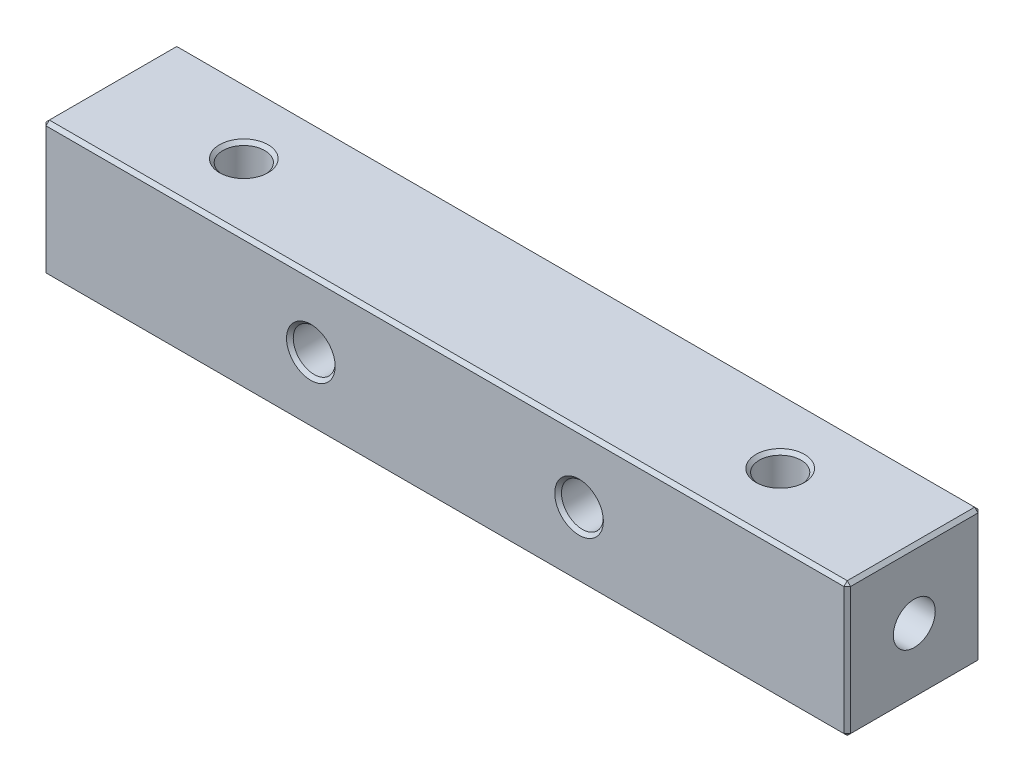
SolidWorks part; units mm, degrees
ref_plane "前视基准面" through (0, 0, 0) normal (0, 0, 1) x (1, 0, 0)
ref_plane "上视基准面" through (0, 0, 0) normal (0, 1, 0) x (1, 0, 0)
ref_plane "右视基准面" through (0, 0, 0) normal (1, 0, 0) x (0, 0, -1)
sketch "草图1" plane through (0, 0, 0) normal (0, 1, 0) x (1, 0, 0)
  line L1 (-24, 4) -> (24, 4)
  line L2 (-24, 4) -> (-24, -4)
  line L3 (-24, -4) -> (24, -4)
  line L4 (24, 4) -> (24, -4)
  line L5 (-24, 4) -> (24, -4) construction
  line L6 (-24, -4) -> (24, 4) construction
  point P0 (0, 0)
  dimension "D1" = 8
  dimension "D2" = 48
extrude "凸台-拉伸1" add sketch "草图1" along normal mid plane 8
hole_wizard "M3 螺纹孔1" positions "草图4" profile "草图6" tap size "M3" standard "GB" end condition through all
sketch "草图4" plane through (0, 4, 0) normal (0, 1, 0) x (1, 0, 0)
  line L0 (-24, 4) -> (-24, -4) construction
  line L1 (0, 0) -> (-50000, 0) construction
  point P0 (-16, 0)
  point P2 (16, 0)
  dimension "D1" = 8
  dimension "D2" = 32
sketch "草图6" plane through (-16, 4, 0) normal (1, 0, 0) x (0, 0, 1)
  line L0 (0, 0) -> (0, 8)
  line L1 (0, 8) -> (1.25, 8)
  line L2 (1.25, 8) -> (1.25, 0)
  line L5 (1.25, 0) -> (0, 0)
  line L11 (0, -6.35) -> (0, 107.95) construction
  dimension "通孔螺纹孔钻头直径" = 2.5
  dimension "通孔螺纹孔钻头深度" = 8
cosmetic thread "孔螺蚊线1"
cosmetic thread "孔螺蚊线2"
hole_wizard "M3 螺纹孔2" positions "草图7" profile "草图8" tap size "M3" standard "GB" end condition through all
sketch "草图7" plane through (0, 0, -4) normal (0, 0, -1) x (-1, 0, 0)
  line L0 (0, 0) -> (-50000, 0) construction
  line L1 (-24, 4) -> (-24, -4) construction
  point P0 (-8, 0)
  point P2 (8, 0)
  dimension "D1" = 16
  dimension "D2" = 16
sketch "草图8" plane through (8, 0, -4) normal (1, 0, 0) x (0, 1, 0)
  line L0 (0, 0) -> (0, 8)
  line L1 (0, 8) -> (1.25, 8)
  line L2 (1.25, 8) -> (1.25, 0)
  line L5 (1.25, 0) -> (0, 0)
  line L11 (0, -6.35) -> (0, 107.95) construction
  dimension "通孔螺纹孔钻头直径" = 2.5
  dimension "通孔螺纹孔钻头深度" = 8
cosmetic thread "孔螺蚊线3"
cosmetic thread "孔螺蚊线4"
chamfer "倒角1" distance 0.2 angle 45 20 edges at (16, -4, 1.25) (-16, -4, 1.25) (-9.25, 0, 4) (6.75, 0, 4) (16, 4, 1.25) (-16, 4, 1.25) (-24, -4, 0) (24, -4, 0) (-24, 0, 4) (0, -4, 4) (24, 0, 4) (0, 4, 4) (-24, 4, 0) (24, 4, 0) (24, 0, -4) (0, 4, -4) (-24, 0, -4) (0, -4, -4) (-9.25, 0, -4) (6.75, 0, -4)
hole_wizard "M3 螺纹孔3" positions "草图9" profile "草图10" tap size "M3" standard "GB"
sketch "草图9" plane through (-24, 0, 0) normal (-1, 0, 0) x (0, 0, 1)
  point P0 (0, 0)
sketch "草图10" plane through (-24, 0, 0) normal (0, 1, 0) x (0, 0, 1)
  line L0 (0, 0) -> (0, 6.75)
  line L1 (0, 6.75) -> (1.25, 6.75)
  line L2 (1.25, 6.75) -> (1.25, 0)
  line L5 (1.25, 0) -> (0, 0)
  line L11 (0, -6.35) -> (0, 107.95) construction
  dimension "通孔螺纹孔钻头直径" = 2.5
  dimension "通孔螺纹孔钻头深度" = 6.75
cosmetic thread "孔螺蚊线5"
hole_wizard "M3 螺纹孔4" positions "草图11" profile "草图12" tap size "M3" standard "GB"
sketch "草图11" plane through (24, 0, 0) normal (1, 0, 0) x (0, 0, -1)
  point P0 (0, 0)
sketch "草图12" plane through (24, 0, 0) normal (0, 1, 0) x (0, 0, -1)
  line L0 (0, 0) -> (0, 6.75)
  line L1 (0, 6.75) -> (1.25, 6.75)
  line L2 (1.25, 6.75) -> (1.25, 0)
  line L5 (1.25, 0) -> (0, 0)
  line L11 (0, -6.35) -> (0, 107.95) construction
  dimension "通孔螺纹孔钻头直径" = 2.5
  dimension "通孔螺纹孔钻头深度" = 6.75
cosmetic thread "孔螺蚊线6"
